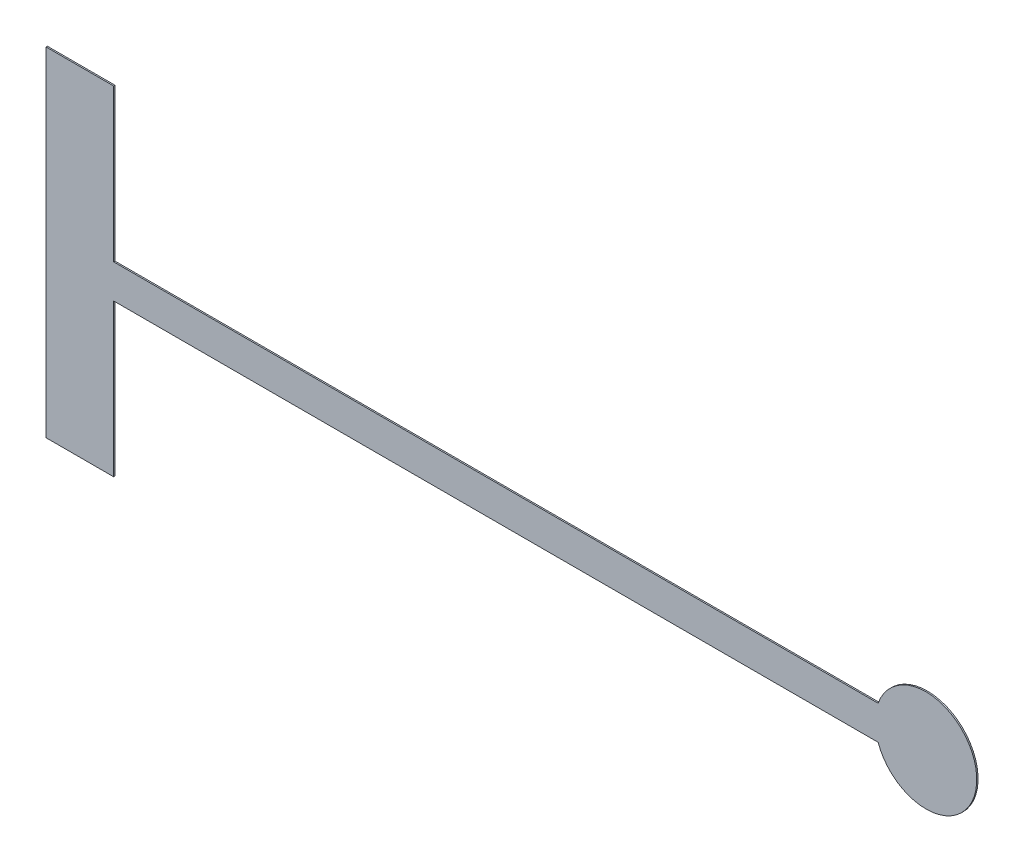
SolidWorks part; units mm, degrees
ref_plane "Front Plane" through (0, 0, 0) normal (0, 0, 1) x (1, 0, 0)
ref_plane "Top Plane" through (0, 0, 0) normal (0, 1, 0) x (1, 0, 0)
ref_plane "Right Plane" through (0, 0, 0) normal (1, 0, 0) x (0, 0, -1)
sketch "Sketch1" plane through (0, 0, 0) normal (0, 0, 1) x (1, 0, 0)
  line L0 (1000, 250) -> (5000, 250)
  line L1 (-1000, 2500) -> (1000, 2500)
  line L2 (-1000, 2500) -> (-1000, -2500)
  line L3 (-1000, -2500) -> (1000, -2500)
  line L4 (1000, 2500) -> (1000, 250)
  line L5 (-1000, 2500) -> (1000, -2500) construction
  line L6 (-1000, -2500) -> (1000, 2500) construction
  line L9 (1000, -250) -> (5000, -250)
  line L10 (5000, 250) -> (5000, 125)
  line L11 (-3000, 250) -> (5000, -250) construction
  line L12 (-3000, -250) -> (5000, 250) construction
  line L13 (5000, 125) -> (9000, 125)
  line L15 (5000, -125) -> (9000, -125)
  line L16 (9000, 125) -> (9000, 100)
  line L17 (1000, 125) -> (9000, -125) construction
  line L18 (1000, -125) -> (9000, 125) construction
  line L19 (9000, 100) -> (11256.6966, 100)
  line L21 (9000, -100) -> (11256.6966, -100)
  line L23 (6000, 100) -> (12000, -100) construction
  line L24 (6000, -100) -> (12000, 100) construction
  line L25 (1000, -250) -> (1000, -2500)
  line L26 (5000, -125) -> (5000, -250)
  line L27 (9000, -100) -> (9000, -125)
  arc A0 (11256.6966, -100) -> (11256.6966, 100) centre (12000, 0) ccw
  point P0 (0, 0)
  point P6 (1000, 0)
  point P11 (5000, 0)
  point P16 (9000, 0)
  dimension "D9" = 1500
  dimension "D1" = 2000
  dimension "D2" = 5000
  dimension "D3" = 500
  dimension "D4" = 4000
  dimension "D5" = 250
  dimension "D6" = 4000
  dimension "D7" = 200
extrude "Boss-Extrude1" add sketch "Sketch1" against normal blind 20
sketch "Sketch2" plane through (0, 0, 0) normal (0, 0, 1) x (1, 0, 0)
  line L0 (0, -11) -> (0, 11) construction
  line L1 (1000, 2500) -> (0, 2500)
  line L2 (1000, 2500) -> (1000, 250)
  line L3 (1000, 250) -> (0, 250)
  line L4 (0, 2500) -> (0, 250)
  line L5 (1000, -2500) -> (0, -2500)
  line L6 (1000, -2500) -> (1000, -250)
  line L7 (1000, -250) -> (0, -250)
  line L8 (0, -2500) -> (0, -250)
  dimension "D1" = 1000
  dimension "D2" = 2250
extrude "Cut-Extrude1" cut sketch "Sketch2" against normal through all
sketch "Sketch3" plane through (0, 0, 0) normal (0, 0, 1) x (1, 0, 0)
  line L0 (0, 0) -> (1098.3807, 0) construction
  line L1 (11, 0) -> (-11, 0) construction
  line L2 (5000, 250) -> (0, 250) construction
  line L3 (1500, 250) -> (3250, 250)
  line L4 (1500, 250) -> (1500, 200)
  line L5 (1500, 200) -> (3250, 200)
  line L7 (0, -250) -> (5000, -250) construction
  line L8 (1500, -250) -> (3250, -250)
  line L9 (1500, -250) -> (1500, -200)
  line L10 (1500, -200) -> (3250, -200)
  line L12 (0, -11) -> (0, 11) construction
  line L13 (3250, 200) -> (3250, 150)
  line L14 (3250, 250) -> (5000, 250)
  line L16 (3250, 150) -> (5000, 150)
  line L17 (5000, 250) -> (5000, 150)
  line L18 (3250, -250) -> (5000, -250)
  line L19 (3250, -200) -> (3250, -150)
  line L20 (3250, -150) -> (5000, -150)
  line L21 (5000, -250) -> (5000, -150)
  point P17 (1500, 225)
  dimension "D1" = 1098.3807
  dimension "D2" = 1750
  dimension "D3" = 50
  dimension "D4" = 1750
  dimension "D5" = 50
  dimension "D6" = 1500
  dimension "D7" = 1500
  dimension "D8" = 100
  dimension "D9" = 100
  dimension "D10" = 1750
  dimension "D11" = 1750
extrude "Cut-Extrude4" cut sketch "Sketch3" against normal through all contours L8 L18 L21 L20 L19 L10 L9
mirror "Mirror1" about plane through (0, 0, 0) normal (0, 1, 0) of "Cut-Extrude4"
sketch "Sketch5" plane through (0, 0, 0) normal (0, 0, 1) x (1, 0, 0)
  line L0 (0, -11) -> (0, 11) construction
  line L1 (0, -250) -> (11500, -250)
  line L2 (0, -250) -> (0, 250)
  line L3 (0, 250) -> (11500, 250)
  line L4 (11500, -250) -> (11500, 250)
  line L5 (0, -250) -> (1500, -250) construction
  dimension "D1" = 500
  dimension "D2" = 11500
extrude "Boss-Extrude2" add sketch "Sketch5" against normal blind 20
